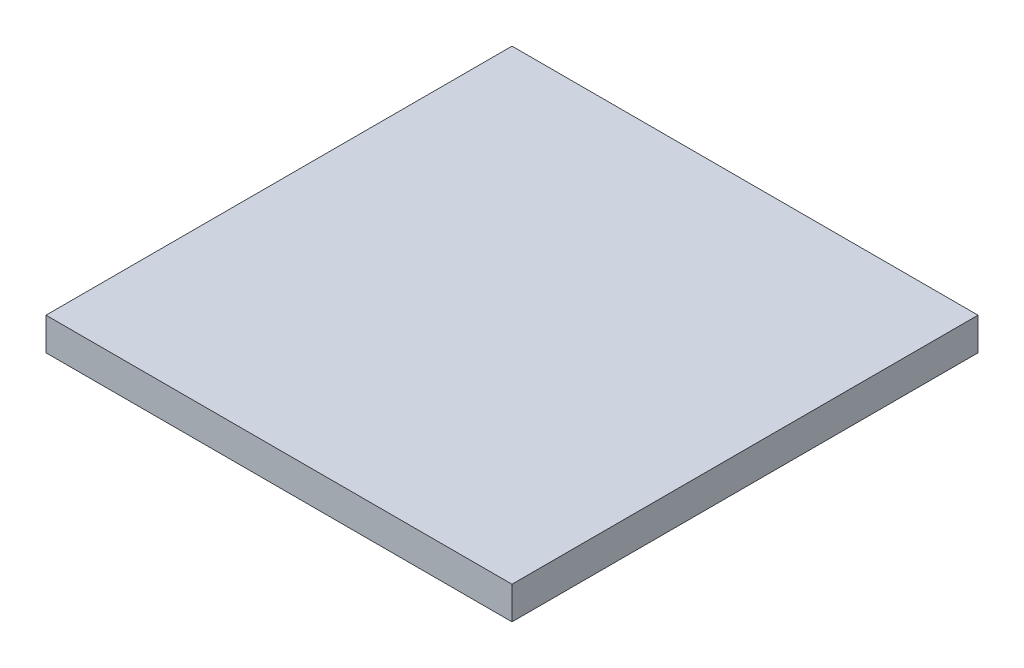
SolidWorks part; units mm, degrees
ref_plane "Front Plane" through (0, 0, 0) normal (0, 0, 1) x (1, 0, 0)
ref_plane "Top Plane" through (0, 0, 0) normal (0, 1, 0) x (1, 0, 0)
ref_plane "Right Plane" through (0, 0, 0) normal (1, 0, 0) x (0, 0, -1)
sketch "Sketch1" plane through (0, 0, 0) normal (0, 1, 0) x (1, 0, 0)
  line L1 (-5, -5) -> (5, -5)
  line L2 (-5, -5) -> (-5, 5)
  line L3 (-5, 5) -> (5, 5)
  line L4 (5, -5) -> (5, 5)
  line L5 (-5, -5) -> (5, 5) construction
  line L6 (-5, 5) -> (5, -5) construction
  point P0 (0, 0)
  dimension "D1" = 10
  dimension "D2" = 10
extrude "Boss-Extrude1" add sketch "Sketch1" along normal blind 0.7
